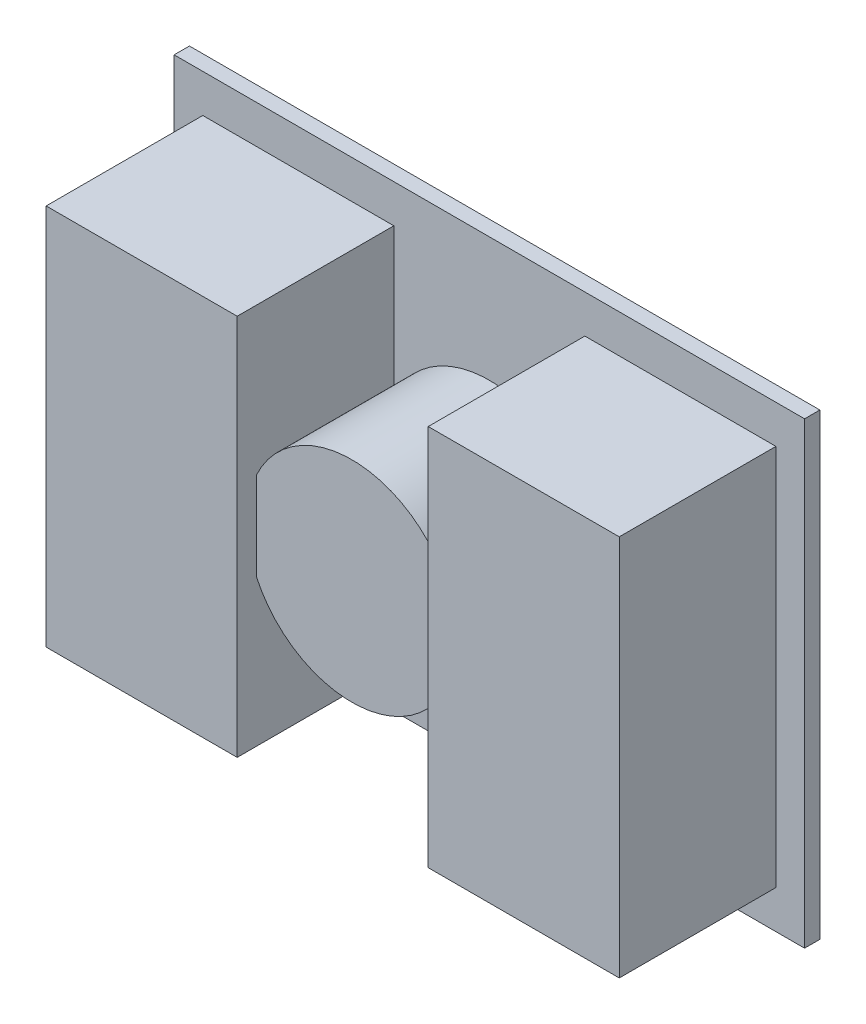
SolidWorks part; units mm, degrees
ref_plane "Front Plane" through (0, 0, 0) normal (0, 0, 1) x (1, 0, 0)
ref_plane "Top Plane" through (0, 0, 0) normal (0, 1, 0) x (1, 0, 0)
ref_plane "Right Plane" through (0, 0, 0) normal (1, 0, 0) x (0, 0, -1)
sketch "Sketch1" plane through (0, 0, 0) normal (0, 0, 1) x (1, 0, 0)
  line L0 (-33, -24) -> (33, -24)
  line L1 (33, -24) -> (33, 24)
  line L2 (33, 24) -> (-33, 24)
  line L3 (-33, 24) -> (-33, -24)
extrude "PCB" add sketch "Sketch1" along normal blind 1.6
ref_plane "P_Front_1p6" through (0, 0, 1.6) normal (0, 0, 1) x (1, 0, 0)
sketch "Sketch2" plane through (0, 0, 1.6) normal (0, 0, 1) x (1, 0, 0)
  line L0 (-30, -20) -> (-10, -20)
  line L1 (-10, -20) -> (-10, 20)
  line L2 (-10, 20) -> (-30, 20)
  line L3 (-30, 20) -> (-30, -20)
extrude "Heatsink_in" add sketch "Sketch2" along normal blind 16.4
sketch "Sketch3" plane through (0, 0, 1.6) normal (0, 0, 1) x (1, 0, 0)
  line L0 (10, -20) -> (30, -20)
  line L1 (30, -20) -> (30, 20)
  line L2 (30, 20) -> (10, 20)
  line L3 (10, 20) -> (10, -20)
extrude "Heatsink_out" add sketch "Sketch3" along normal blind 16.4
sketch "Sketch4" plane through (0, 0, 1.6) normal (0, 0, 1) x (1, 0, 0)
  circle A0 centre (0, 0) radius 11
extrude "Inductor" add sketch "Sketch4" along normal blind 14.4
